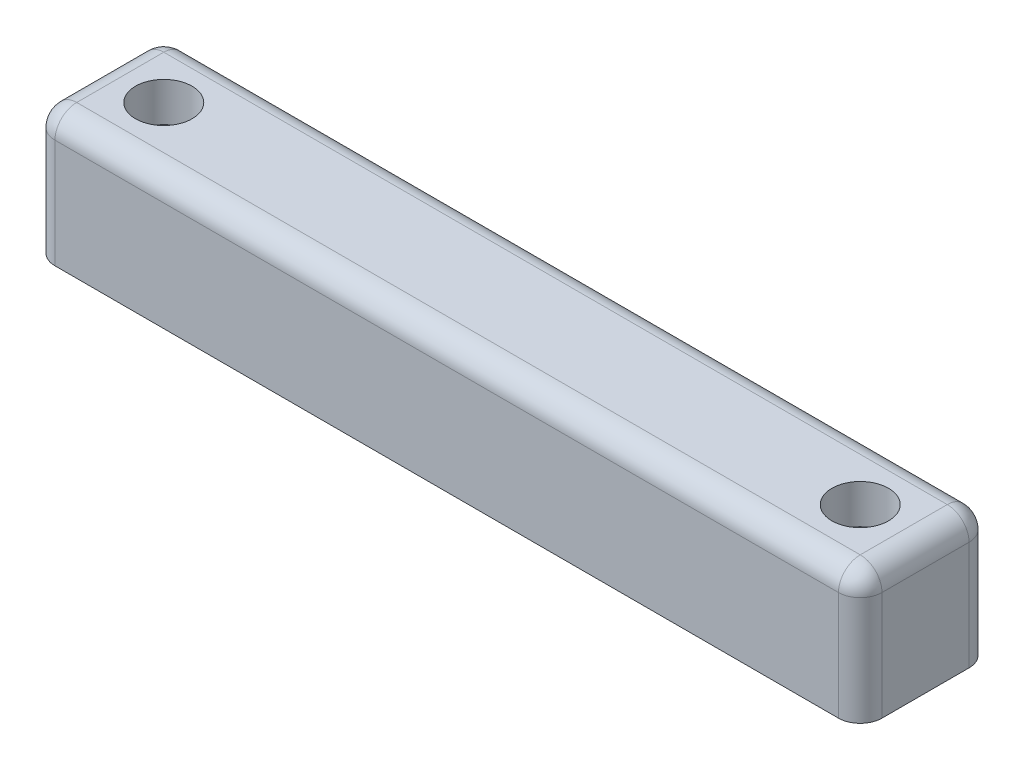
SolidWorks part; units mm, degrees
material "POM Acetal Copolymer"
ref_plane "Front Plane" through (0, 0, 0) normal (0, 0, 1) x (1, 0, 0)
ref_plane "Top Plane" through (0, 0, 0) normal (0, 1, 0) x (1, 0, 0)
ref_plane "Right Plane" through (0, 0, 0) normal (1, 0, 0) x (0, 0, -1)
sketch "Sketch1" plane through (0, 0, 0) normal (0, 0, 1) x (1, 0, 0)
  line L1 (95, -15) -> (-95, -15)
  line L2 (95, -15) -> (95, 15)
  line L3 (95, 15) -> (-95, 15)
  line L4 (-95, -15) -> (-95, 15)
  line L5 (95, -15) -> (-95, 15) construction
  line L6 (95, 15) -> (-95, -15) construction
  point P0 (0, 0)
  dimension "D1" = 30
  dimension "D2" = 190
extrude "Boss-Extrude1" add sketch "Sketch1" along normal mid plane 30
fillet "Fillet3" radius 5 8 edges at (95, 15, 0) (0, 15, 15) (-95, 15, 0) (0, 15, -15) (-95, 0, -15) (-95, 0, 15) (95, 0, -15) (95, 0, 15)
hole_wizard "CBORE for M6 Hex Socket Head Cap Screw1" positions "Sketch3" profile "Sketch2" counterbore size "M6" standard "ISO" end condition through all
sketch "Sketch3" plane through (0, 15, 0) normal (0, 1, 0) x (1, 0, 0)
  line L0 (-80, 0) -> (80, 0) construction
  line L1 (95, 10) -> (95, -10) construction
  point P0 (-80, 0)
  point P10 (80, 0)
  dimension "D1" = 15
sketch "Sketch2" plane through (-80, 15, 0) normal (1, 0, 0) x (0, 0, 1)
  line L0 (0, 0) -> (0, 30)
  line L1 (0, 30) -> (3.3, 30)
  line L3 (3.3, 30) -> (3.3, 9)
  line L4 (3.3, 9) -> (6.5, 9)
  line L5 (6.5, 9) -> (6.5, 0)
  line L7 (6.5, 0) -> (0, 0)
  line L11 (0, -6.35) -> (0, 107.95) construction
  dimension "Thru Hole Dia." = 6.6
  dimension "Thru Hole Depth" = 30
  dimension "C'Bore Dia." = 13
  dimension "C'Bore Depth" = 9
